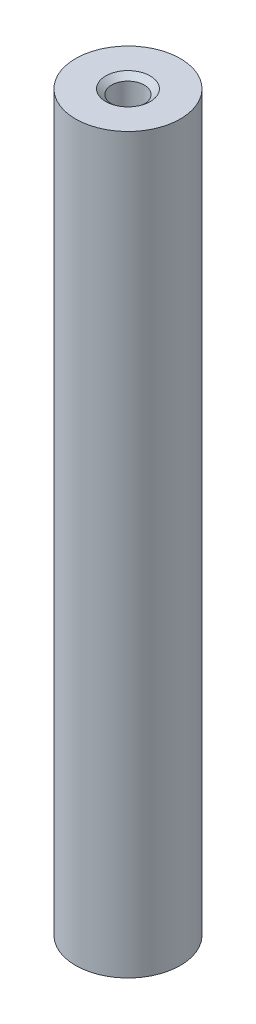
SolidWorks part; units mm, degrees
material "AISI 304"
ref_plane "Front" through (0, 0, 0) normal (0, 0, 1) x (1, 0, 0)
ref_plane "Top" through (0, 0, 0) normal (0, 1, 0) x (1, 0, 0)
ref_plane "Right" through (0, 0, 0) normal (1, 0, 0) x (0, 0, -1)
sketch "Sketch1" plane through (0, 0, 0) normal (0, 1, 0) x (1, 0, 0)
  circle A0 centre (0, 0) radius 12.7
  dimension "D1" = 25.4
extrude "Boss-Extrude1" add sketch "Sketch1" along normal blind 177.8
hole_wizard "1/2-13 Tapped Hole1" positions "Sketch2" profile "Sketch3" tap size "1/2-13" standard "ANSI Inch"
sketch "Sketch2" plane through (0, 0, 0) normal (0, -1, 0) x (-1, 0, 0)
  point P0 (0, 0)
sketch "Sketch3" plane through (0, 0, 0) normal (1, 0, 0) x (0, 0, -1)
  line L0 (0, 0) -> (0, 28.6195)
  line L1 (0, 28.6195) -> (5.3581, 25.4)
  line L2 (5.3581, 25.4) -> (5.3581, 1.3651)
  line L3 (5.3581, 1.3651) -> (6.985, 0)
  line L5 (6.985, 0) -> (0, 0)
  line L6 (-5.3581, 1.3651) -> (-6.985, 0) construction
  line L10 (0, 28.6195) -> (-5.3581, 25.4) construction
  line L11 (0, -6.35) -> (0, 107.95) construction
  dimension "Tap Drill Dia." = 10.7163
  dimension "Tap Drill Depth" = 25.4
  dimension "Near C'Sink Dia." = 13.97
  dimension "Near C'Sink Angle" = 100
  dimension "Drill Angle" = 118
cosmetic thread "Hole Thread1"
hole_wizard "3/8-16 Tapped Hole1" positions "Sketch4" profile "Sketch5" tap size "3/8-16" standard "ANSI Inch"
sketch "Sketch4" plane through (0, 177.8, 0) normal (0, 1, 0) x (1, 0, 0)
  point P0 (0, 0)
sketch "Sketch5" plane through (0, 177.8, 0) normal (1, 0, 0) x (0, 0, 1)
  line L0 (0, 0) -> (0, 27.7847)
  line L1 (0, 27.7847) -> (3.9687, 25.4)
  line L2 (3.9687, 25.4) -> (3.9687, 1.1989)
  line L3 (3.9687, 1.1989) -> (5.3975, 0)
  line L5 (5.3975, 0) -> (0, 0)
  line L6 (-3.9687, 1.1989) -> (-5.3975, 0) construction
  line L10 (0, 27.7847) -> (-3.9688, 25.4) construction
  line L11 (0, -6.35) -> (0, 107.95) construction
  dimension "Tap Drill Dia." = 7.9375
  dimension "Tap Drill Depth" = 25.4
  dimension "Near C'Sink Dia." = 10.795
  dimension "Near C'Sink Angle" = 100
  dimension "Drill Angle" = 118
cosmetic thread "Hole Thread2"
